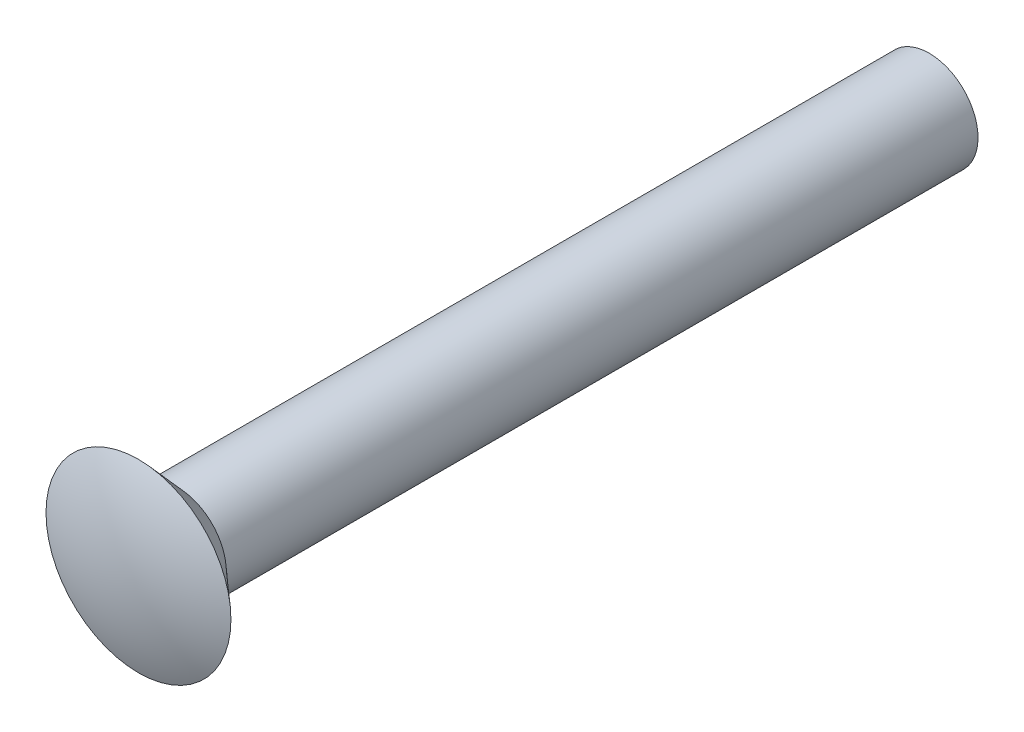
SolidWorks part; units mm, degrees
ref_plane "Спереди" through (0, 0, 0) normal (0, 0, 1) x (1, 0, 0)
ref_plane "Сверху" through (0, 0, 0) normal (0, 1, 0) x (1, 0, 0)
ref_plane "Справа" through (0, 0, 0) normal (1, 0, 0) x (0, 0, -1)
other "Configuration Table"
sketch "Эскиз1" plane through (0, 0, 0) normal (1, 0, 0) x (0, 0, -1)
  line L0 (0, 0) -> (66.6667, 0) construction
  line L2 (5.4544, 5) -> (82.4544, 5)
  line L3 (83.4544, 0) -> (-0.5456, 0)
  line L4 (66.6667, 0) -> (83.4544, 0) construction
  line L5 (83.4544, 0) -> (83.4544, 3)
  line L6 (82.4544, 5) -> (83.4544, 3)
  line L7 (5.4544, 5) -> (1.4544, 9.4721)
  arc A0 (1.4544, 9.4721) -> (-0.5456, 0) centre (22.8847, 0) ccw
  point P4 (0, 0)
  dimension "D1" = 5
  dimension "D2" = 1
  dimension "D3" = 2
  dimension "D4" = 6
  dimension "D5" = 77
  dimension "D6" = 3
  dimension "D7" = 82.4544
  dimension "D8" = 6
  dimension "D9" = 84
  dimension "D10" = 66.6667
revolve "Повернуть1" add sketch "Эскиз1" angle 360 about L3
